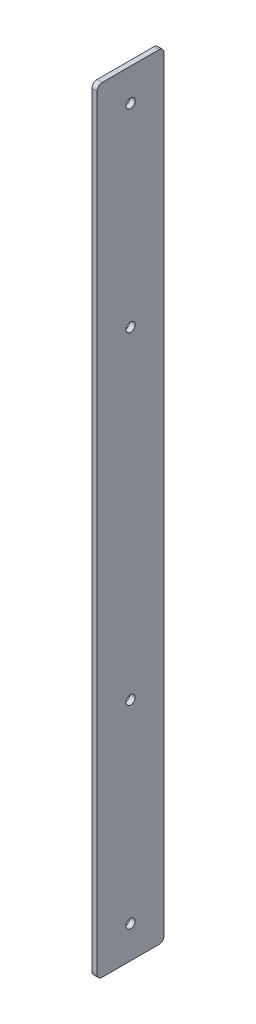
SolidWorks part; units mm, degrees
material "6061-T6 (SS)"
ref_plane "Front Plane" through (0, 0, 0) normal (0, 0, 1) x (1, 0, 0)
ref_plane "Top Plane" through (0, 0, 0) normal (0, 1, 0) x (1, 0, 0)
ref_plane "Right Plane" through (0, 0, 0) normal (1, 0, 0) x (0, 0, -1)
sketch "Sketch1" plane through (0, 0, 0) normal (1, 0, 0) x (0, 0, -1)
  line L1 (-13, -150) -> (13, -150)
  line L2 (-13, -150) -> (-13, 150)
  line L3 (-13, 150) -> (13, 150)
  line L4 (13, -150) -> (13, 150)
  line L5 (-13, -150) -> (13, 150) construction
  line L6 (-13, 150) -> (13, -150) construction
  point P0 (0, 0)
  dimension "D1" = 300
  dimension "D2" = 26
extrude "Boss-Extrude1" add sketch "Sketch1" along normal blind 2
fillet "Fillet1" radius 2 4 edges at (1, -150, -13) (1, -150, 13) (1, 150, -13) (1, 150, 13)
sketch "Sketch2" plane through (2, 0, 0) normal (1, 0, 0) x (0, 0, -1)
  line L0 (0, 150) -> (0, 137.5) construction
  line L1 (0, 137.5) -> (0, 62.5) construction
  line L2 (1.1, 0) -> (-1.1, 0) construction
  line L4 (-11, -150) -> (11, -150)
  line L5 (13, -148) -> (13, 148)
  line L6 (11, 150) -> (-11, 150)
  line L7 (-13, 148) -> (-13, -148)
  line L8 (-11, -150) -> (11, -150)
  line L9 (13, -148) -> (13, 148)
  line L10 (11, 150) -> (-11, 150)
  line L11 (-13, 148) -> (-13, -148)
  circle A0 centre (0, 137.5) radius 1.75
  circle A1 centre (0, 62.5) radius 1.75
  circle A2 centre (0, -62.5) radius 1.75
  circle A3 centre (0, -137.5) radius 1.75
  arc A4 (11, -150) -> (13, -148) centre (11, -148) ccw
  arc A5 (13, 148) -> (11, 150) centre (11, 148) ccw
  arc A6 (-11, 150) -> (-13, 148) centre (-11, 148) ccw
  arc A7 (-13, -148) -> (-11, -150) centre (-11, -148) ccw
  arc A8 (11, -150) -> (13, -148) centre (11, -148) ccw
  arc A9 (13, 148) -> (11, 150) centre (11, 148) ccw
  arc A10 (-11, 150) -> (-13, 148) centre (-11, 148) ccw
  arc A11 (-13, -148) -> (-11, -150) centre (-11, -148) ccw
  dimension "D3" = 3.5
  dimension "D2" = 12.5
  dimension "D4" = 75
  dimension "D1" = 0
extrude "Cut-Extrude1" cut sketch "Sketch2" against normal through all contours A3 | A2 | A1 | A0
